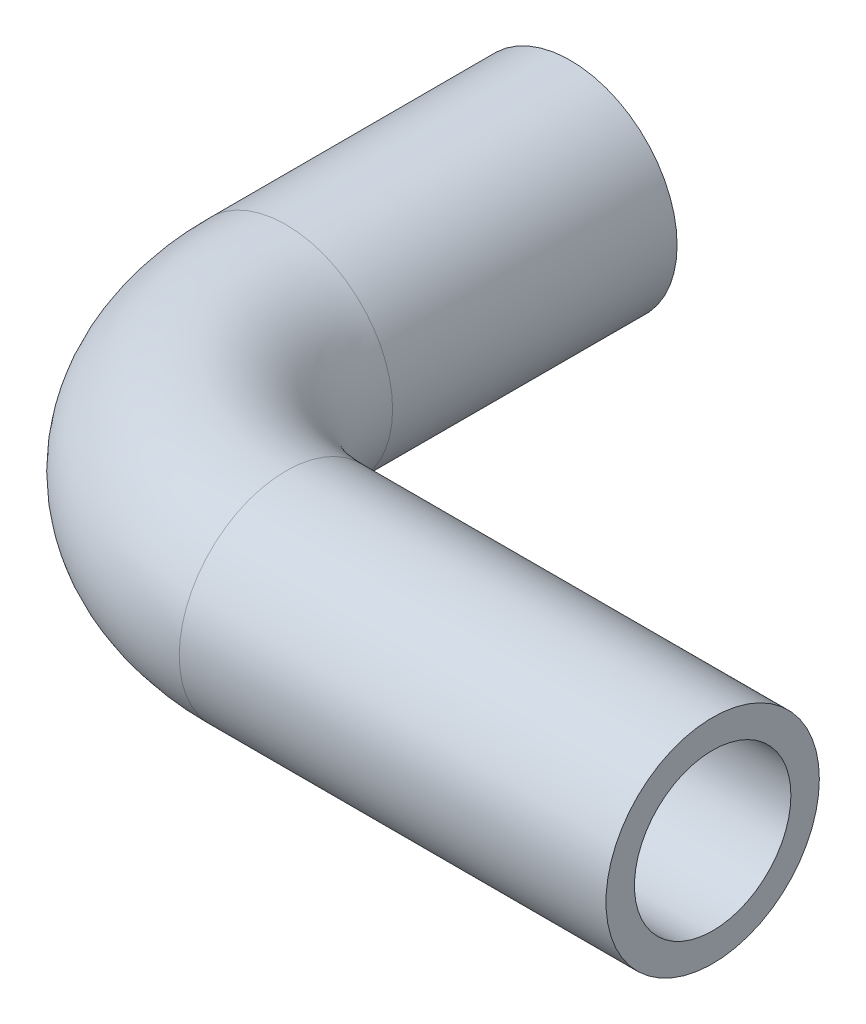
SolidWorks part; units mm, degrees
material "Plain Carbon Steel"
ref_plane "Front Plane" through (0, 0, 0) normal (0, 0, 1) x (1, 0, 0)
ref_plane "Top Plane" through (0, 0, 0) normal (0, 1, 0) x (1, 0, 0)
ref_plane "Right Plane" through (0, 0, 0) normal (1, 0, 0) x (0, 0, -1)
sketch "Sketch2" plane through (0, 0, 0) normal (0, 1, 0) x (1, 0, 0)
  line L0 (0, 0) -> (150, 0)
  line L1 (-75, 175) -> (-75, 75)
  arc A0 (-75, 75) -> (0, 0) centre (0, 75) ccw
  dimension "D1" = 150
  dimension "D2" = 75
  dimension "D3" = 75
  dimension "D4" = 100
sketch "Sketch3" plane through (0, 0, 0) normal (1, 0, 0) x (0, 0, -1)
  circle A0 centre (0, 0) radius 37.5
  dimension "D1" = 75
sweep "Sweep1" add path "Sketch2" circular profile diameter 75 parameters "D3"=75
shell "Shell1" thickness 10
sketch "Sketch4" plane through (0, 0, -175) normal (0, 0, -1) x (-1, 0, 0)
  line L0 (75, 27.5) -> (75, 37.5)
  circle A0 centre (75, 0) radius 27.5
  circle A1 centre (75, 0) radius 37.5 construction
  dimension "D1" = 10
extrude "Cut-Extrude1" cut sketch "Sketch4" against normal up to next contours A0
